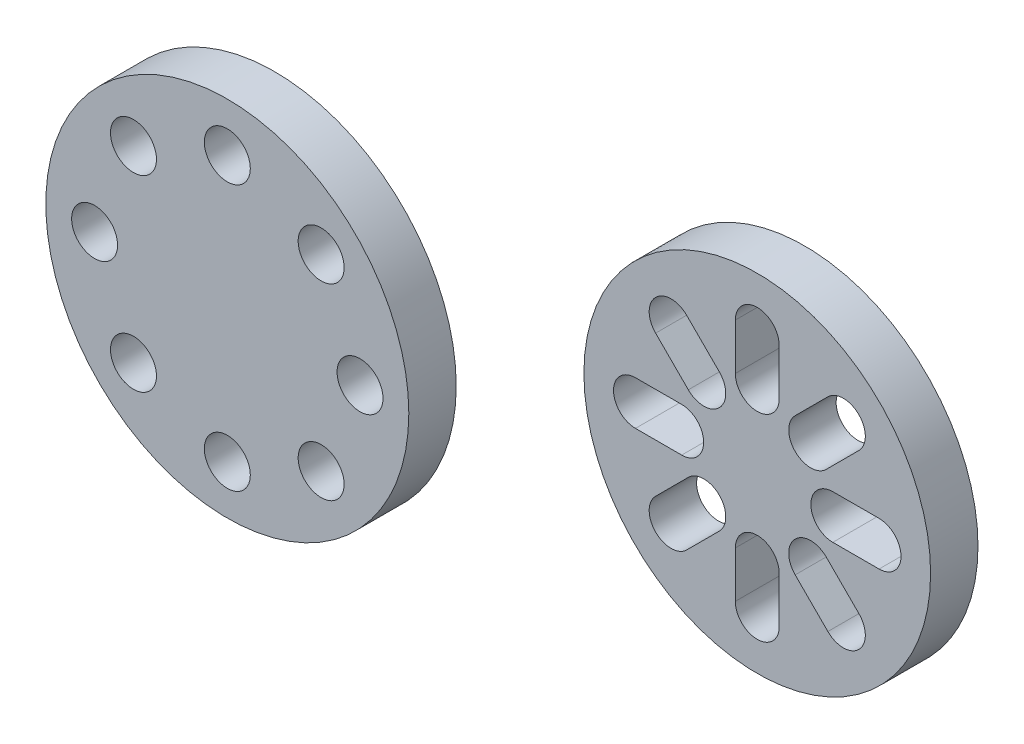
SolidWorks part; units mm, degrees
ref_plane "Front Plane" through (0, 0, 0) normal (0, 0, 1) x (1, 0, 0)
ref_plane "Top Plane" through (0, 0, 0) normal (0, 1, 0) x (1, 0, 0)
ref_plane "Right Plane" through (0, 0, 0) normal (1, 0, 0) x (0, 0, -1)
sketch "Sketch1" plane through (0, 0, 0) normal (0, 0, 1) x (1, 0, 0)
  line L0 (127.7576, 25.7964) -> (137.517, 25.7964) construction
  line L1 (127.7576, 30.4256) -> (137.517, 30.4256)
  line L2 (127.7576, 21.1672) -> (137.517, 21.1672)
  line L3 (123.0885, 14.5244) -> (129.9895, 7.6234) construction
  line L4 (126.3618, 17.7977) -> (133.2628, 10.8967)
  line L5 (119.8152, 11.251) -> (126.7161, 4.3501)
  line L6 (111.8164, 9.8553) -> (111.8164, 0.0959) construction
  line L7 (116.4456, 9.8553) -> (116.4456, 0.0959)
  line L8 (107.1873, 9.8553) -> (107.1873, 0.0959)
  line L9 (100.5444, 14.5244) -> (93.6434, 7.6234) construction
  line L10 (103.8177, 11.251) -> (96.9168, 4.3501)
  line L11 (97.2711, 17.7977) -> (90.3701, 10.8967)
  line L12 (95.8753, 25.7964) -> (86.1159, 25.7964) construction
  line L13 (95.8753, 21.1672) -> (86.1159, 21.1672)
  line L14 (95.8753, 30.4256) -> (86.1159, 30.4256)
  line L15 (100.5444, 37.0685) -> (93.6434, 43.9694) construction
  line L16 (97.2711, 33.7952) -> (90.3701, 40.6961)
  line L17 (103.8177, 40.3418) -> (96.9168, 47.2428)
  line L18 (111.8164, 41.7375) -> (111.8164, 51.4969) construction
  line L19 (107.1873, 41.7375) -> (107.1873, 51.4969)
  line L20 (116.4456, 41.7375) -> (116.4456, 51.4969)
  line L21 (123.0885, 37.0685) -> (129.9895, 43.9694) construction
  line L22 (119.8152, 40.3418) -> (126.7161, 47.2428)
  line L23 (126.3618, 33.7952) -> (133.2628, 40.6961)
  circle A0 centre (0, 0) radius 38.2986
  circle A1 centre (28.0021, 0) radius 4.8492
  circle A2 centre (19.8004, -19.8004) radius 4.8492
  circle A3 centre (0, -28.0021) radius 4.8492
  circle A4 centre (-19.8004, -19.8004) radius 4.8492
  circle A5 centre (-28.0021, 0) radius 4.8492
  circle A6 centre (-19.8004, 19.8004) radius 4.8492
  circle A7 centre (0, 28.0021) radius 4.8492
  circle A8 centre (19.8004, 19.8004) radius 4.8492
  circle A9 centre (111.8164, 25.7964) radius 36.5771
  arc A10 (127.7576, 30.4256) -> (127.7576, 21.1672) centre (127.7576, 25.7964) ccw
  arc A11 (137.517, 21.1672) -> (137.517, 30.4256) centre (137.517, 25.7964) ccw
  arc A12 (126.3618, 17.7977) -> (119.8152, 11.251) centre (123.0885, 14.5244) ccw
  arc A13 (126.7161, 4.3501) -> (133.2628, 10.8967) centre (129.9895, 7.6234) ccw
  arc A14 (116.4456, 9.8553) -> (107.1873, 9.8553) centre (111.8164, 9.8553) ccw
  arc A15 (107.1873, 0.0959) -> (116.4456, 0.0959) centre (111.8164, 0.0959) ccw
  arc A16 (103.8177, 11.251) -> (97.2711, 17.7977) centre (100.5444, 14.5244) ccw
  arc A17 (90.3701, 10.8967) -> (96.9168, 4.3501) centre (93.6434, 7.6234) ccw
  arc A18 (95.8753, 21.1672) -> (95.8753, 30.4256) centre (95.8753, 25.7964) ccw
  arc A19 (86.1159, 30.4256) -> (86.1159, 21.1672) centre (86.1159, 25.7964) ccw
  arc A20 (97.2711, 33.7952) -> (103.8177, 40.3418) centre (100.5444, 37.0685) ccw
  arc A21 (96.9168, 47.2428) -> (90.3701, 40.6961) centre (93.6434, 43.9694) ccw
  arc A22 (107.1873, 41.7375) -> (116.4456, 41.7375) centre (111.8164, 41.7375) ccw
  arc A23 (116.4456, 51.4969) -> (107.1873, 51.4969) centre (111.8164, 51.4969) ccw
  arc A24 (119.8152, 40.3418) -> (126.3618, 33.7952) centre (123.0885, 37.0685) ccw
  arc A25 (133.2628, 40.6961) -> (126.7161, 47.2428) centre (129.9895, 43.9694) ccw
  point P21 (0, 0)
  point P24 (132.6373, 25.7964)
  point P34 (126.539, 11.0739)
  point P41 (111.8164, 4.9756)
  point P48 (97.0939, 11.0739)
  point P55 (90.9956, 25.7964)
  point P62 (97.0939, 40.519)
  point P69 (111.8164, 46.6172)
  point P76 (126.539, 40.519)
  point P81 (111.8164, 25.7964)
extrude "Boss-Extrude1" add sketch "Sketch1" along normal blind 10
